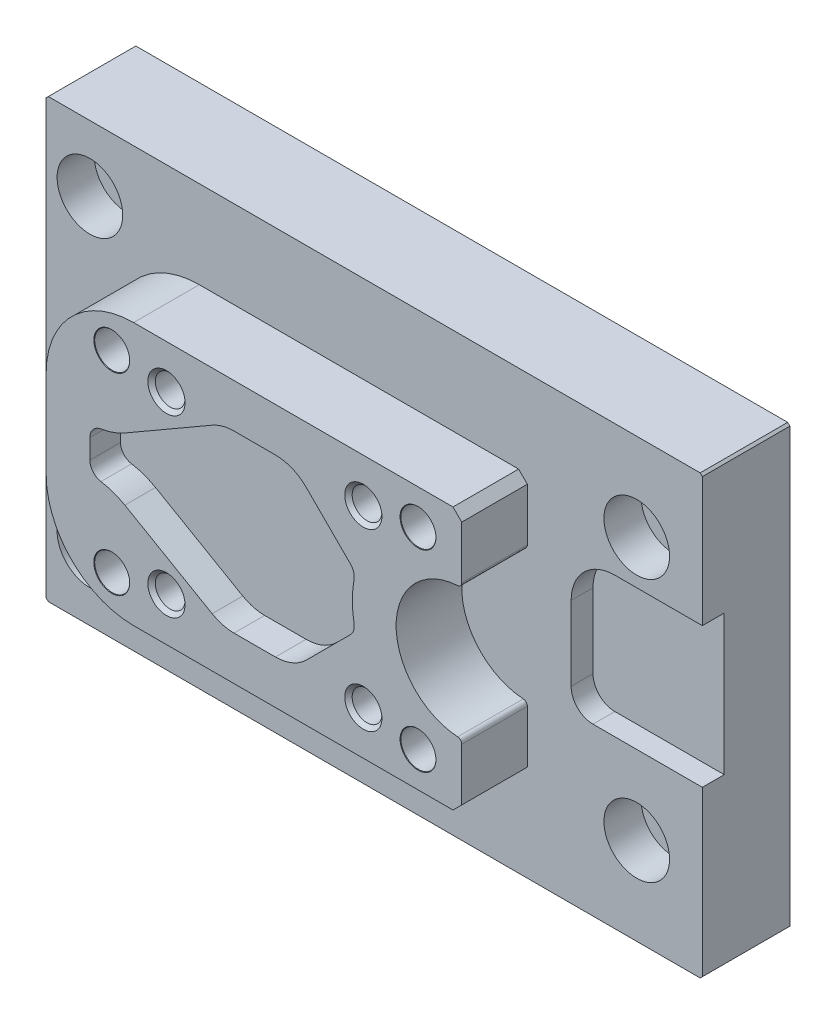
SolidWorks part; units mm, degrees
material "1060 Alloy"
ref_plane "Front Plane" through (0, 0, 0) normal (0, 0, 1) x (1, 0, 0)
ref_plane "Top Plane" through (0, 0, 0) normal (0, 1, 0) x (1, 0, 0)
ref_plane "Right Plane" through (0, 0, 0) normal (1, 0, 0) x (0, 0, -1)
sketch "Sketch1" plane through (0, 0, 0) normal (0, 0, 1) x (1, 0, 0)
  line L1 (-50, 50) -> (100, 50)
  line L2 (-50, 50) -> (-50, -50)
  line L3 (-50, -50) -> (100, -50)
  line L4 (100, 50) -> (100, -50)
  circle A0 centre (0, 0) radius 50 construction
  dimension "D1" = 150
  dimension "D2" = 100
extrude "Extrude1" add sketch "Sketch1" along normal blind 20
sketch "Sketch2" plane through (0, 0, 20) normal (0, 0, 1) x (1, 0, 0)
  line L0 (60, -15) -> (60, -30)
  line L1 (-35, 30) -> (60, 30)
  line L2 (-35, 30) -> (-35, -30)
  line L3 (-35, -30) -> (60, -30)
  line L4 (60, 30) -> (60, 15)
  line L5 (-50, 50) -> (-50, -50) construction
  line L6 (100, -50) -> (100, 50) construction
  arc A0 (60, 15) -> (60, -15) centre (60, 0) ccw
  dimension "D3" = 15
  dimension "D1" = 15
  dimension "D2" = 40
  dimension "D4" = 60
extrude "Extrude2" add sketch "Sketch2" along normal blind 15
fillet "Fillet1" radius 20 2 edges at (-35, 30, 27.5) (-35, -30, 27.5)
hole_wizard "CBORE for M8 Hex Socket Head Cap Screw1" positions "3DSketch1" profile "Sketch4" counterbore size "M8" standard "ISO" end condition through all
sketch3d "3DSketch1"
  line L1 (-50, 50, 20) -> (-50, -50, 20) construction
  line L2 (-50, -50, 20) -> (100, -50, 20) construction
  line L3 (100, -50, 20) -> (100, 50, 20) construction
  point P0 (-40, -35, 20)
  point P3 (85, -30, 20)
  dimension "D1" = 10
  dimension "D2" = 15
  dimension "D3" = 15
  dimension "D4" = 20
sketch "Sketch4" plane through (-40, -35, 20) normal (1, 0, 0) x (0, -1, 0)
  line L0 (0, 0) -> (0, 20)
  line L1 (0, 20) -> (4.5, 20)
  line L2 (4.5, 8.525) -> (4.5, 20)
  line L3 (4.5, 8.525) -> (4.525, 8.5)
  line L4 (4.525, 8.5) -> (7.5, 8.5)
  line L5 (7.5, 8.5) -> (7.5, 0)
  line L7 (0, 0) -> (7.5, 0)
  line L9 (-4.5, 8.525) -> (-4.525, 8.5) construction
  line L11 (0, -6.35) -> (0, 107.95) construction
  dimension "Thru Hole Dia." = 9
  dimension "Thru Hole Depth" = 20
  dimension "C'Bore Dia." = 15
  dimension "C'Bore Depth" = 8.5
  dimension "Mid C'Sink Dia." = 9.05
  dimension "Mid C'Sink Angle" = 90
hole_wizard "M8 Tapped Hole1" positions "3DSketch2" profile "Sketch7" tap size "M8" standard "ISO"
sketch3d "3DSketch2"
  line L0 (-15, -30, 35) -> (60, -30, 35) construction
  line L1 (-35, 10, 35) -> (-35, -10, 35) construction
  line L2 (60, -30, 35) -> (60, -15, 35) construction
  point P0 (-7.5, -20, 35)
  point P2 (37.5, -20, 35)
  dimension "D1" = 10
  dimension "D2" = 27.5
  dimension "D3" = 22.5
sketch "Sketch7" plane through (-7.5, -20, 35) normal (1, 0, 0) x (0, -1, 0)
  line L0 (0, 0) -> (0, 24.2929)
  line L1 (0, 24.2929) -> (3.4, 22.25)
  line L2 (3.4, 22.25) -> (3.4, 0.85)
  line L3 (3.4, 0.85) -> (4.25, 0)
  line L5 (4.25, 0) -> (0, 0)
  line L6 (-3.4, 0.85) -> (-4.25, 0) construction
  line L10 (0, 24.2929) -> (-3.4, 22.25) construction
  line L11 (0, -6.35) -> (0, 107.95) construction
  dimension "Tap Drill Dia." = 6.8
  dimension "Tap Drill Depth" = 22.25
  dimension "Near C'Sink Dia." = 8.5
  dimension "Near C'Sink Angle" = 90
  dimension "Drill Angle" = 118
cosmetic thread "Hole Thread1" parameters "D1"=16, "D2"=8
cosmetic thread "Hole Thread2" parameters "D1"=16, "D2"=8
hole_wizard "Ø8.0 (8) Diameter Hole1" positions "3DSketch3" profile "Sketch8" hole size "Ø8.0" standard "ISO"
sketch3d "3DSketch3"
  line L0 (-35, 10, 35) -> (-35, -10, 35) construction
  line L1 (60, -30, 35) -> (60, -15, 35) construction
  line L2 (-15, -30, 35) -> (60, -30, 35) construction
  point P0 (-20, -22, 35)
  point P2 (50, -22, 35)
  dimension "D1" = 15
  dimension "D2" = 10
  dimension "D3" = 8
sketch "Sketch8" plane through (-20, -22, 35) normal (1, 0, 0) x (0, -1, 0)
  line L0 (0, 0) -> (0, 22.4034)
  line L1 (0, 22.4034) -> (4, 20)
  line L2 (4, 20) -> (4, 0.1)
  line L3 (4, 0.1) -> (4.1, 0)
  line L5 (4.1, 0) -> (0, 0)
  line L6 (-4, 0.1) -> (-4.1, 0) construction
  line L10 (0, 22.4034) -> (-4, 20) construction
  line L11 (0, -6.35) -> (0, 107.95) construction
  dimension "Hole Dia." = 8
  dimension "Hole Depth" = 20
  dimension "Near C'Sink Dia." = 8.2
  dimension "Near C'Sink Angle" = 90
  dimension "Drill Angle" = 118
mirror "Mirror1" about plane through (0, 0, 0) normal (0, 1, 0) of "Ø8.0 (8) Diameter Hole1", "CBORE for M8 Hex Socket Head Cap Screw1", "M8 Tapped Hole1"
ref_point "Point1"
ref_point "Point2"
sketch "Sketch5" plane through (0, 0, 20) normal (0, 0, 1) x (1, 0, 0)
  line L4 (107, 10) -> (107, 57)
  line L8 (-57, 57) -> (-57, -57)
  line L9 (-57, -57) -> (107, -57)
  line L10 (107, -57) -> (107, 57)
  line L11 (107, 57) -> (-57, 57)
  line L12 (-57, 57) -> (-57, -57)
  line L13 (-57, -57) -> (107, -57)
  line L14 (107, -57) -> (107, -10)
  line L15 (107, 57) -> (-57, 57)
  arc A0 (107, -10) -> (107, 10) centre (107, 0) ccw
  dimension "D2" = 10
  dimension "D1" = 7
sketch "Sketch9" plane through (0, 0, 35) normal (0, 0, 1) x (1, 0, 0)
  line L5 (21.5538, 20) -> (35.696, 5.8579)
  line L6 (21.5538, -20) -> (35.696, -5.8579)
  line L7 (-17, 7.1436) -> (5.2679, 20)
  line L8 (5.2679, -20) -> (-17, -7.1436)
  line L10 (45, 20) -> (-15, 20)
  line L11 (-25, 10) -> (-25, -10)
  line L12 (-15, -20) -> (45, -20)
  line L13 (21.5538, 20) -> (5.2679, 20)
  line L14 (-25, 5) -> (-25, -5)
  line L15 (5.2679, -20) -> (21.5538, -20)
  arc A3 (-25, -5) -> (-17, -7.1436) centre (-25, -21) cw
  arc A4 (-17, 7.1436) -> (-25, 5) centre (-25, 21) cw
  arc A6 (-15, 20) -> (-25, 10) centre (-15, 10) ccw
  arc A7 (-25, -10) -> (-15, -20) centre (-15, -10) ccw
  arc A8 (45, 20) -> (45, -20) centre (60, 0) ccw
  arc A11 (35.696, 5.8579) -> (35.696, -5.8579) centre (60, 0) ccw
  dimension "D2" = 16
  dimension "D3" = 45
  dimension "D4" = 20
  dimension "D5" = 30
  dimension "D6" = 10
  dimension "D1" = 10
extrude "Extrude3" cut sketch "Sketch9" against normal blind 7
fillet "Fillet2" radius 3 4 edges at (35.696, -5.8579, 31.5) (35.696, 5.8579, 31.5) (-25, -5, 31.5) (-25, 5, 31.5)
fillet "Fillet3" radius 10 4 edges at (5.2679, -20, 31.5) (21.5538, -20, 31.5) (21.5538, 20, 31.5) (5.2679, 20, 31.5)
chamfer "Chamfer1" distance 0.5 angle 45 4 edges at (-50, 50, 10) (100, 50, 10) (-50, -50, 10) (100, -50, 10)
chamfer "Chamfer2" distance 2 angle 45 2 edges at (60, 30, 27.5) (60, -30, 27.5)
fillet "Fillet4" radius 1 2 edges at (60, -15, 27.5) (60, 15, 27.5)
sketch "Sketch10" plane through (0, 0, 20) normal (0, 0, 1) x (1, 0, 0)
  line L0 (100, -49.5) -> (100, 49.5) construction
  line L1 (70, 20) -> (100, 20)
  line L2 (70, 20) -> (70, -12)
  line L3 (70, -12) -> (100, -12)
  line L4 (100, 20) -> (100, -12)
  dimension "D1" = 12
  dimension "D2" = 20
  dimension "D3" = 30
extrude "Extrude4" cut sketch "Sketch10" against normal blind 5
fillet "Fillet5" radius 10 1 edges at (70, 20, 17.5)
fillet "Fillet6" radius 5 1 edges at (70, -12, 17.5)
sketch "Sketch11" plane through (0, 0, 0) normal (0, 0, -1) x (-1, 0, 0)
  circle A0 centre (40, -35) radius 5
  circle A1 centre (-85, -30) radius 5
  circle A2 centre (-85, 30) radius 5
  circle A3 centre (40, 35) radius 5
  circle A4 centre (40, -35) radius 4.5 construction
  circle A5 centre (-85, -30) radius 4.5 construction
  circle A6 centre (-85, 30) radius 4.5 construction
  circle A7 centre (40, 35) radius 4.5 construction
  dimension "D1" = 10
extrude "Extrude5" cut sketch "Sketch11" against normal blind 1
